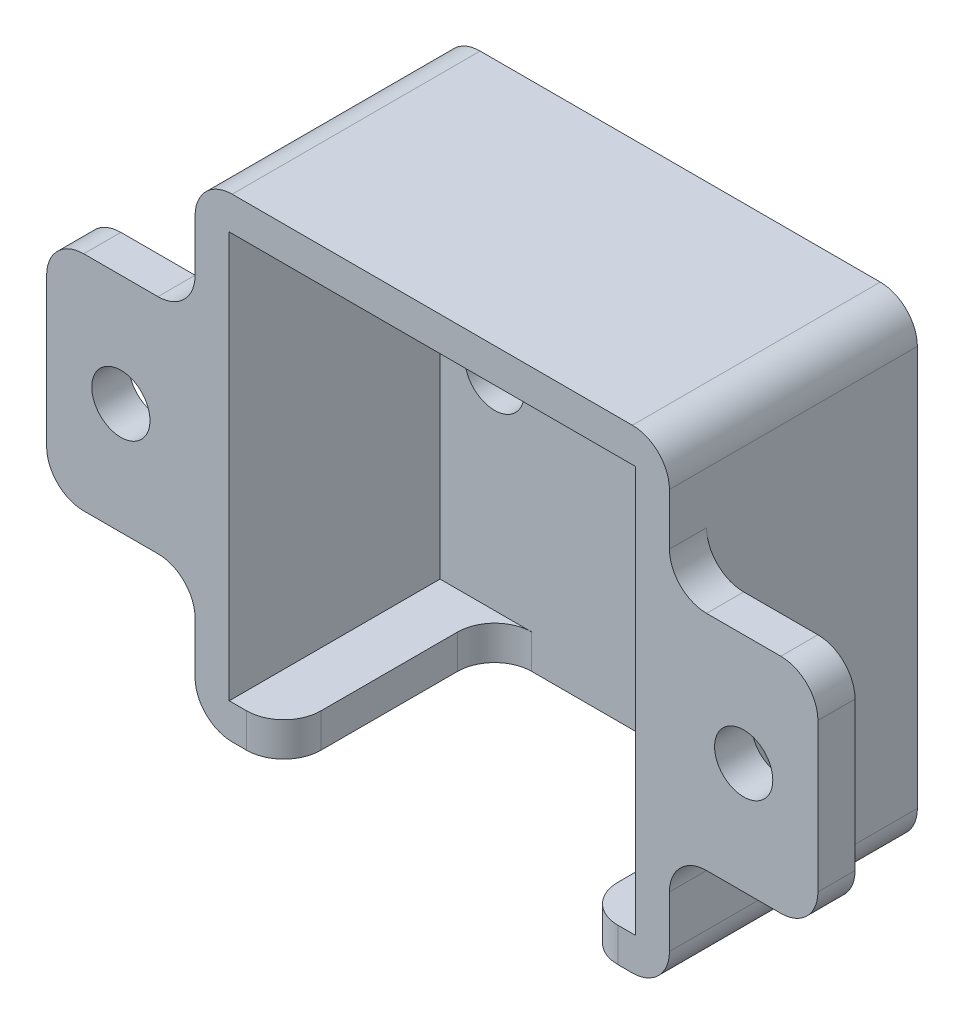
SolidWorks part; units mm, degrees
material "PET"
ref_plane "Front Plane" through (0, 0, 0) normal (0, 0, 1) x (1, 0, 0)
ref_plane "Top Plane" through (0, 0, 0) normal (0, 1, 0) x (1, 0, 0)
ref_plane "Right Plane" through (0, 0, 0) normal (1, 0, 0) x (0, 0, -1)
sketch "Sketch1" plane through (0, 0, 0) normal (0, 0, 1) x (1, 0, 0)
  line L1 (-20.2889, -20.2889) -> (20.2889, -20.2889)
  line L2 (-20.2889, -20.2889) -> (-20.2889, 20.2889)
  line L3 (-20.2889, 20.2889) -> (20.2889, 20.2889)
  line L4 (20.2889, -20.2889) -> (20.2889, 20.2889)
  line L5 (-20.2889, -20.2889) -> (20.2889, 20.2889) construction
  line L6 (-20.2889, 20.2889) -> (20.2889, -20.2889) construction
  line L11 (-13.9389, -13.9389) -> (13.9389, 13.9389) construction
  line L12 (-13.9389, 13.9389) -> (13.9389, -13.9389) construction
  circle A0 centre (-12.7, 0) radius 2.54
  circle A1 centre (12.7, 0) radius 2.54
  point P0 (0, 0)
  point P6 (0, 0)
  point P15 (-10.9842, 0.4962)
  point P16 (0, 0)
  point P17 (-14.9671, 0)
  dimension "D2" = 5.08
  dimension "D1" = 40.5778
  dimension "D3" = 7.5889
  dimension "D4" = 7.5889
extrude "Boss-Extrude1" add sketch "Sketch1" along normal mid plane 3.175
sketch "Sketch3" plane through (0, 0, 1.5875) normal (0, 0, 1) x (1, 0, 0)
  line L0 (20.2889, -20.2889) -> (20.2889, 20.2889) construction
  line L1 (-20.2889, -20.2889) -> (20.2889, -20.2889) construction
  line L2 (-20.2889, 20.2889) -> (-20.2889, -20.2889) construction
  line L3 (20.2889, 20.2889) -> (-20.2889, 20.2889) construction
  line L4 (20.2889, -20.2889) -> (20.2889, 20.2889)
  line L5 (-20.2889, -20.2889) -> (20.2889, -20.2889)
  line L6 (-20.2889, 20.2889) -> (-20.2889, -20.2889)
  line L7 (20.2889, 20.2889) -> (-20.2889, 20.2889)
  line L8 (-17.3679, 17.3679) -> (-17.3679, -17.3679)
  line L9 (-17.3679, -17.3679) -> (17.3679, -17.3679)
  line L10 (17.3679, -17.3679) -> (17.3679, 17.3679)
  line L11 (17.3679, 17.3679) -> (-17.3679, 17.3679)
  dimension "D1" = 2.921
extrude "Boss-Extrude2" add sketch "Sketch3" along normal blind 18.034
sketch "Sketch4" plane through (0, 0, 19.6215) normal (0, 0, 1) x (1, 0, 0)
  line L0 (-20.2889, 20.2889) -> (-20.2889, -20.2889) construction
  line L1 (-20.2889, -9.525) -> (-32.9889, -9.525)
  line L2 (-20.2889, -9.525) -> (-20.2889, 9.525)
  line L3 (-20.2889, 9.525) -> (-32.9889, 9.525)
  line L4 (-32.9889, -9.525) -> (-32.9889, 9.525)
  line L5 (20.2889, -20.2889) -> (20.2889, 20.2889) construction
  line L6 (20.2889, -9.525) -> (32.9889, -9.525)
  line L7 (20.2889, -9.525) -> (20.2889, 9.525)
  line L8 (20.2889, 9.525) -> (32.9889, 9.525)
  line L9 (32.9889, -9.525) -> (32.9889, 9.525)
  circle A0 centre (-26.6389, 0) radius 2.4892
  circle A1 centre (26.6389, 0) radius 2.4892
  point P16 (0, 0)
  point P17 (0, 0)
  point P18 (0, 0)
  point P20 (-28.6463, 0)
  point P21 (-36.7815, -9.2715)
  point P22 (-32.9889, 0)
  point P23 (32.9889, 0)
  point P24 (-36.4353, 7.172)
  dimension "D1" = 4.9784
  dimension "D5" = 6.35
  dimension "D6" = 6.35
  dimension "D2" = 6.35
  dimension "D3" = 6.35
  dimension "D4" = 19.05
extrude "Boss-Extrude3" add sketch "Sketch4" against normal blind 3.175
fillet "Fillet1" radius 3.175 12 edges at (-20.2889, -20.2889, 9.017) (-20.2889, -9.525, 18.034) (-32.9889, -9.525, 18.034) (-32.9889, 9.525, 18.034) (-20.2889, 9.525, 18.034) (20.2889, 20.2889, 9.017) (20.2889, 9.525, 18.034) (32.9889, 9.525, 18.034) (32.9889, -9.525, 18.034) (20.2889, -9.525, 18.034) (20.2889, -20.2889, 9.017) (-20.2889, 20.2889, 9.017)
sketch "Sketch6" plane through (0, -20.2889, 0) normal (0, -1, 0) x (1, 0, 0)
  line L1 (-12.7, 19.6215) -> (12.7, 19.6215)
  line L2 (-12.7, 19.6215) -> (-12.7, 1.5875)
  line L3 (-12.7, 1.5875) -> (12.7, 1.5875)
  line L4 (12.7, 19.6215) -> (12.7, 1.5875)
  line L6 (-17.1139, 19.6215) -> (17.1139, 19.6215) construction
  line L7 (-17.1139, -1.5875) -> (17.1139, -1.5875) construction
  point P7 (-12.7, 16.4465)
  point P8 (0, 19.6215)
  point P12 (-12.7, 13.1863)
  point P15 (-12.7, 3.2756)
  dimension "D1" = 25.4
  dimension "D2" = 3.175
extrude "Cut-Extrude2" cut sketch "Sketch6" against normal blind 3.175
fillet "Fillet3" radius 3.175 4 edges at (12.7, -18.8284, 19.6215) (12.7, -18.8284, 1.5875) (-12.7, -18.8284, 1.5875) (-12.7, -18.8284, 19.6215)
equation "\"D1@Sketch1\"=1.347550+(0.25)"
